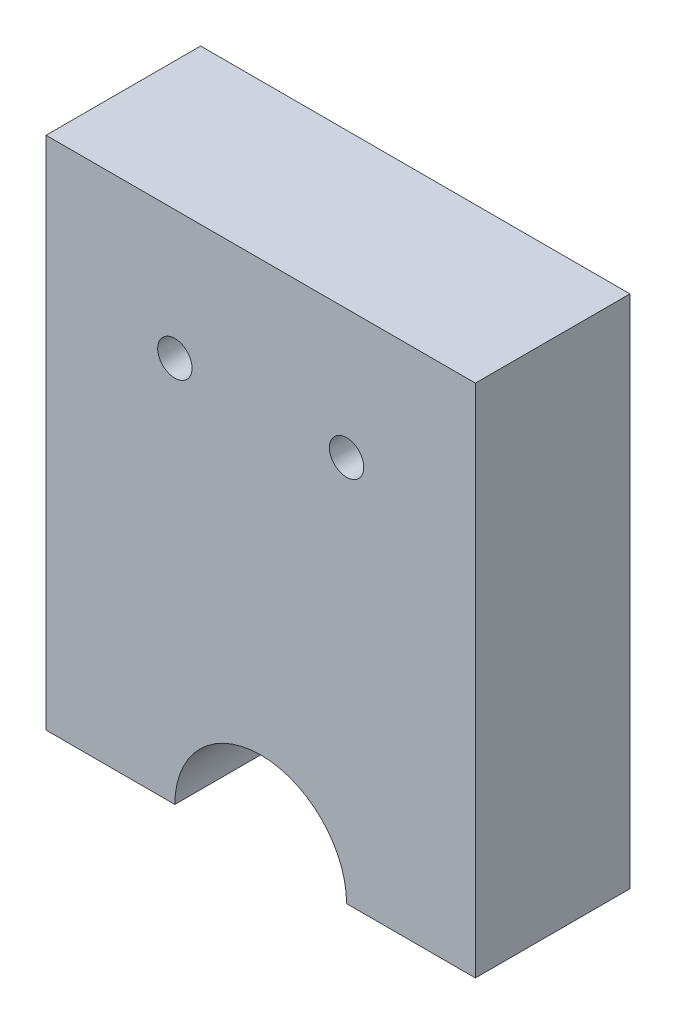
SolidWorks part; units mm, degrees
material "Mahogany"
ref_plane "Plan de face" through (0, 0, 0) normal (0, 0, 1) x (1, 0, 0)
ref_plane "Plan de dessus" through (0, 0, 0) normal (0, 1, 0) x (1, 0, 0)
ref_plane "Plan de droite" through (0, 0, 0) normal (1, 0, 0) x (0, 0, -1)
sketch "Sketch1" plane through (0, 0, 0) normal (0, 0, 1) x (1, 0, 0)
  line L1 (0, 0) -> (25, 0)
  line L2 (0, 0) -> (0, 30)
  line L3 (0, 30) -> (25, 30)
  line L4 (25, 0) -> (25, 30)
  dimension "D1" = 30
  dimension "D2" = 25
extrude "Boss-Extrude1" add sketch "Sketch1" along normal blind 9
sketch "Sketch4" plane through (0, 0, 9) normal (0, 0, 1) x (1, 0, 0)
  line L0 (0, 0) -> (25, 0) construction
  line L1 (0, 0) -> (25, 0)
  circle A0 centre (12.5, 0) radius 5
  dimension "D1" = 10
extrude "Cut-Extrude3" cut sketch "Sketch4" against normal through all contours L1 A0
sketch "Sketch5" plane through (0, 0, 9) normal (0, 0, 1) x (1, 0, 0)
  line L0 (12.5, 30) -> (12.5, 0) construction
  line L1 (25, 30) -> (0, 30) construction
  line L2 (-4.9885, 22.5) -> (28.5895, 22.5) construction
  circle A0 centre (7.5, 22.5) radius 1
  circle A1 centre (17.5, 22.5) radius 1
  dimension "D2" = 2
  dimension "D1" = 7.5
  dimension "D3" = 5
extrude "Cut-Extrude4" cut sketch "Sketch5" against normal through all
